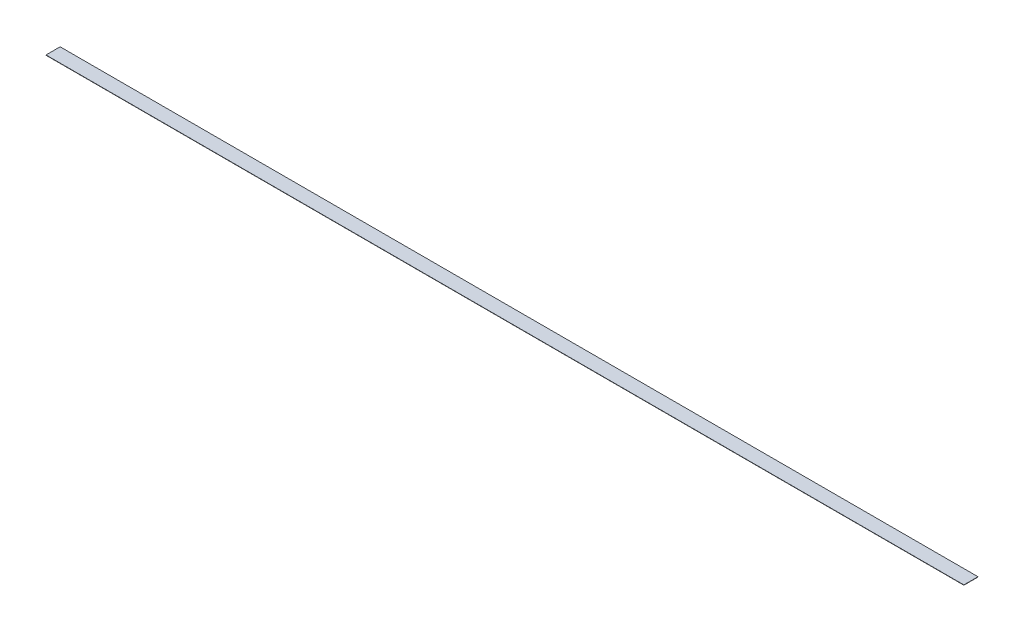
SolidWorks part; units mm, degrees
material "Acrylic (Medium-high impact)"
ref_plane "Front Plane" through (0, 0, 0) normal (0, 0, 1) x (1, 0, 0)
ref_plane "Top Plane" through (0, 0, 0) normal (0, 1, 0) x (1, 0, 0)
ref_plane "Right Plane" through (0, 0, 0) normal (1, 0, 0) x (0, 0, -1)
sketch "Sketch1" plane through (0, 0, 0) normal (0, 0, 1) x (1, 0, 0)
  line L0 (0, 0.0635) -> (206.375, 0) construction
  line L1 (0, 0) -> (206.375, 0) construction
  line L2 (0, 0) -> (0, 0.0635) construction
  line L3 (0, 0.0635) -> (206.375, 0.0635) construction
  line L4 (206.375, 0) -> (206.375, 0.0635) construction
  line L6 (0.0635, 0.0635) -> (206.3115, 0.0635)
  line L7 (0.0635, 0.0635) -> (0.0635, 0)
  line L8 (0.0635, 0) -> (206.3115, 0)
  line L9 (206.3115, 0.0635) -> (206.3115, 0)
  line L10 (0.0635, 0.0635) -> (206.3115, 0) construction
  line L11 (0.0635, 0) -> (206.3115, 0.0635) construction
  point P5 (103.1875, 0.0317)
  dimension "D1" = 0.0635
  dimension "D2" = 206.375
  dimension "D3" = 0.127
  dimension "D4" = 0.0635
extrude "Boss-Extrude1" add sketch "Sketch1" along normal blind 3.175
fillet "Fillet1" [suppressed] radius 0.7937
sketch "Sketch2" plane through (0, 0, 3.175) normal (0, 0, 1) x (1, 0, 0)
  line L0 (205.0415, 0) -> (205.0415, -1.2065) construction
  line L3 (206.3115, 0) -> (206.3115, 0.0635) construction
  line L4 (0.0635, 0) -> (206.3115, 0) construction
  line L5 (206.3115, 0.0635) -> (0.0635, 0.0635) construction
  text T0 "window_short_5/1000\"" font "Consolas" height 3.5
  dimension "D1" = 1.27
  dimension "D2" = 1.27
extrude "Cut-Extrude1" [suppressed] cut sketch "Sketch2" against normal blind 1.27
